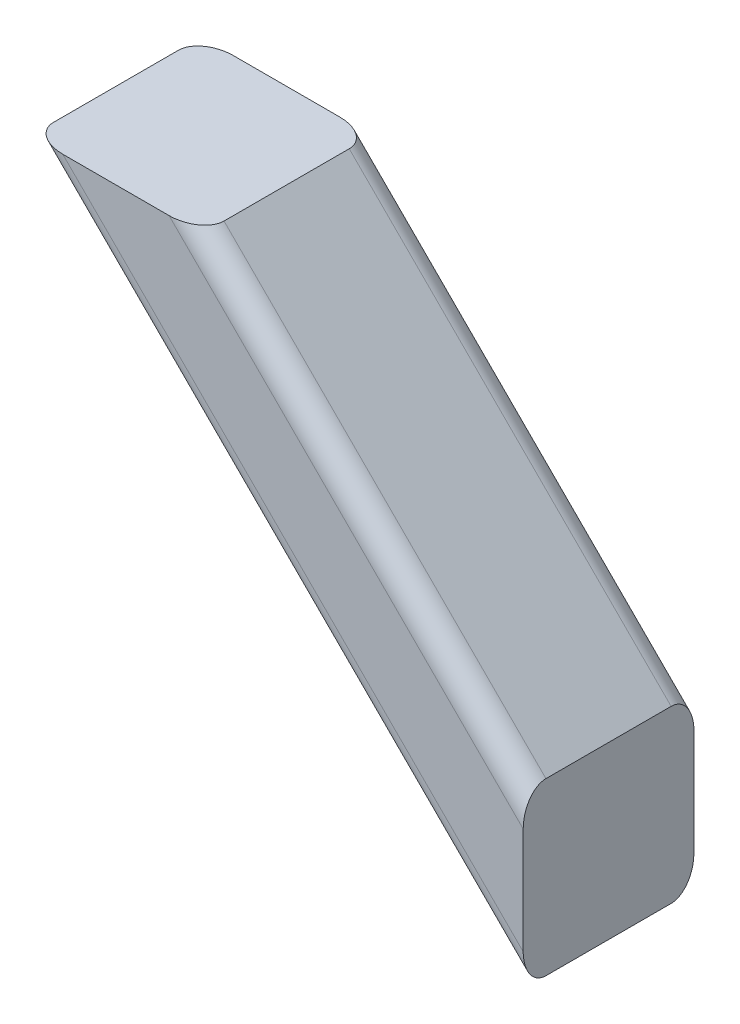
SolidWorks part; units mm, degrees
ref_plane "Front Plane" through (0, 0, 0) normal (0, 0, 1) x (1, 0, 0)
ref_plane "Top Plane" through (0, 0, 0) normal (0, 1, 0) x (1, 0, 0)
ref_plane "Right Plane" through (0, 0, 0) normal (1, 0, 0) x (0, 0, -1)
sketch "Sketch1" plane through (0, 0, 0) normal (0, 0, 1) x (1, 0, 0)
  line L0 (0, 0) -> (0, 15)
  line L1 (0, 15) -> (-28.2843, 43.2843)
  line L2 (-28.2843, 43.2843) -> (-43.2843, 43.2843)
  line L3 (-43.2843, 43.2843) -> (0, 0)
  dimension "D1" = 15
  dimension "D2" = 135
  dimension "D3" = 40
extrude "Boss-Extrude1" add sketch "Sketch1" along normal blind 15
fillet "Fillet1" radius 2 4 edges at (-21.6421, 21.6421, 0) (-14.1421, 29.1421, 0) (-14.1421, 29.1421, 15) (-21.6421, 21.6421, 15)
